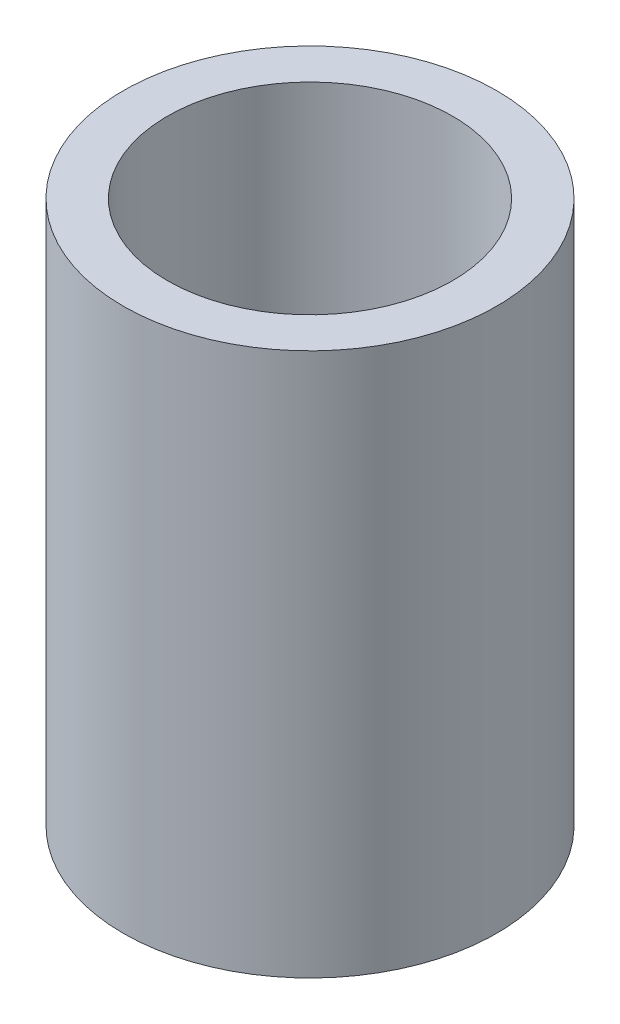
SolidWorks part; units mm, degrees
ref_plane "Front Plane" through (0, 0, 0) normal (0, 0, 1) x (1, 0, 0)
ref_plane "Top Plane" through (0, 0, 0) normal (0, 1, 0) x (1, 0, 0)
ref_plane "Right Plane" through (0, 0, 0) normal (1, 0, 0) x (0, 0, -1)
sketch "Sketch1" plane through (0, 0, 0) normal (0, 1, 0) x (1, 0, 0)
  circle A0 centre (0, 0) radius 4.2
  circle A1 centre (0, 0) radius 5.5
  dimension "D1" = 11
  dimension "D2" = 8.4
extrude "Boss-Extrude1" add sketch "Sketch1" along normal blind 16
